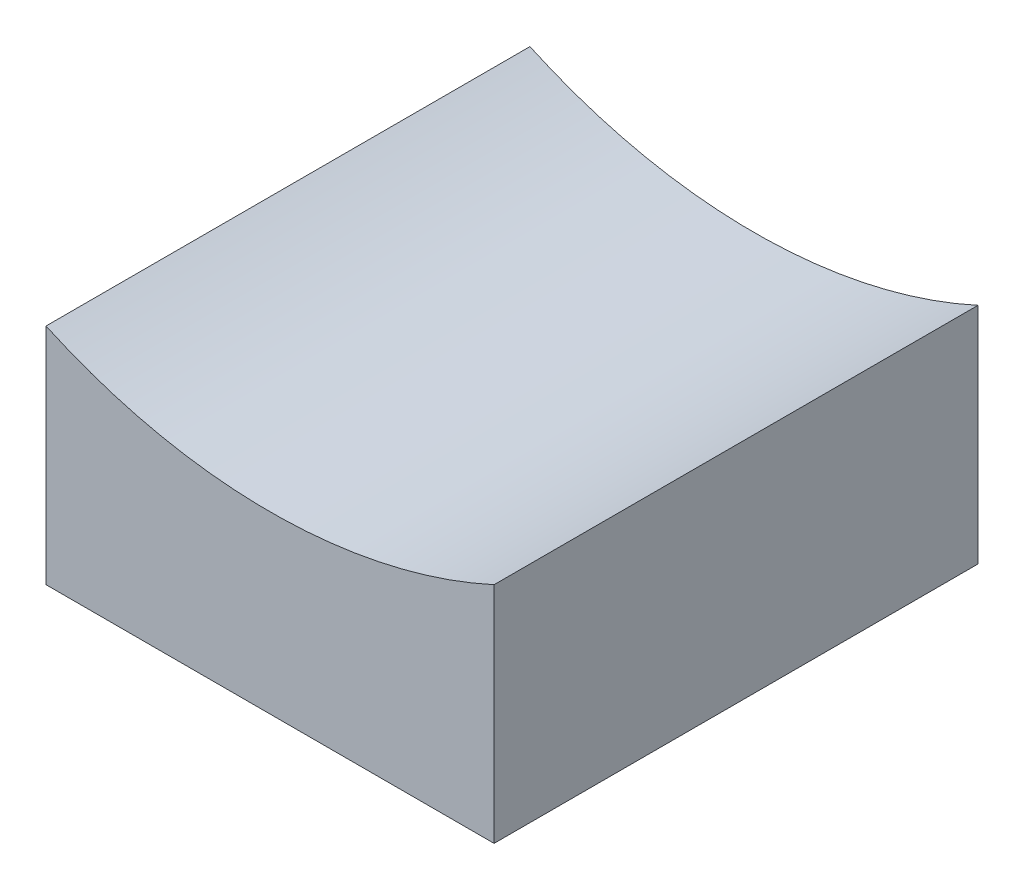
SolidWorks part; units mm, degrees
ref_plane "Front Plane" through (0, 0, 0) normal (0, 0, 1) x (1, 0, 0)
ref_plane "Top Plane" through (0, 0, 0) normal (0, 1, 0) x (1, 0, 0)
ref_plane "Right Plane" through (0, 0, 0) normal (1, 0, 0) x (0, 0, -1)
sketch "Sketch2" plane through (0, 0, 0) normal (0, 0, 1) x (1, 0, 0)
  line L1 (0, 0) -> (50, 0)
  line L2 (0, 0) -> (0, 25)
  line L4 (50, 0) -> (50, 25)
  arc A0 (0, 25) -> (50, 25) centre (25, 79.5436) ccw
  point P1 (28.2896, 80.0898)
  point P2 (0, 0)
  point P8 (58.1727, 0)
  point P9 (58.1727, 15.1774)
  point P10 (0, 15.1774)
  point P11 (0, 0)
  point P12 (25, 0)
  point P13 (0, 20.0974)
  dimension "D1" = 60
  dimension "D2" = 25
  dimension "D3" = 50
extrude "Boss-Extrude1" add sketch "Sketch2" along normal blind 54
